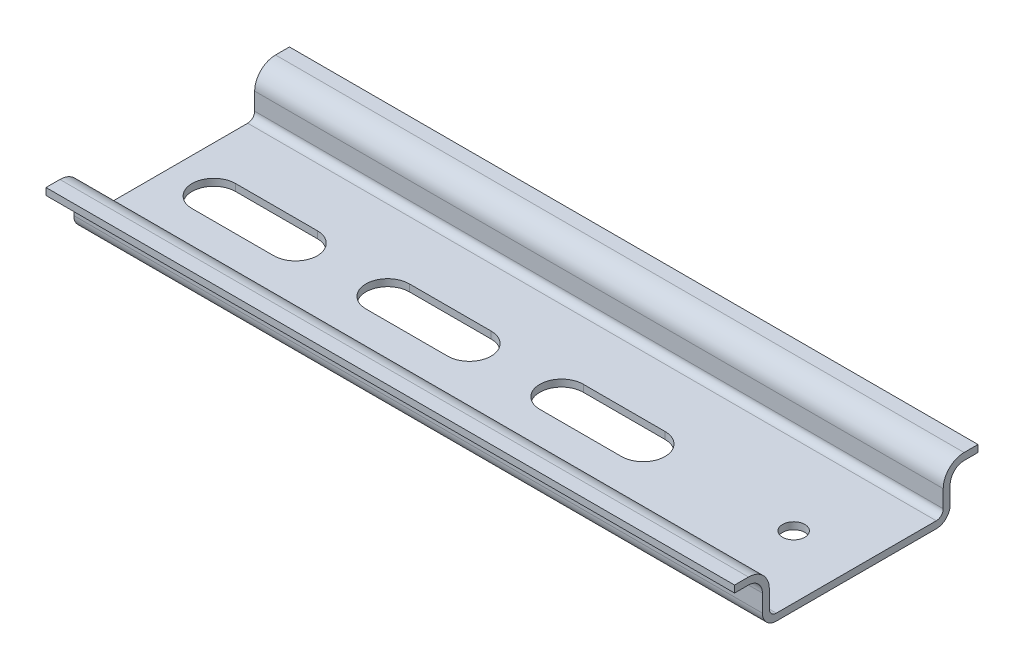
SolidWorks part; units mm, degrees
ref_plane "Front Plane" through (0, 0, 0) normal (0, 0, 1) x (1, 0, 0)
ref_plane "Top Plane" through (0, 0, 0) normal (0, 1, 0) x (1, 0, 0)
ref_plane "Right Plane" through (0, 0, 0) normal (1, 0, 0) x (0, 0, -1)
sketch "Sketch1" plane through (0, 0, 0) normal (1, 0, 0) x (0, 0, -1)
  line L0 (0, 0) -> (0, 18.2344) construction
  line L1 (0, 0) -> (26.621, 0) construction
  line L2 (-11.5, 0) -> (11.5, 0)
  line L3 (13.5, 2) -> (13.5, 4.5)
  line L4 (15.5, 6.5) -> (17.5, 6.5)
  line L5 (-13.5, 2) -> (-13.5, 4.5)
  line L6 (-15.5, 6.5) -> (-17.5, 6.5)
  arc A0 (13.5, 2) -> (11.5, 0) centre (11.5, 2) cw
  arc A1 (15.5, 6.5) -> (13.5, 4.5) centre (15.5, 4.5) ccw
  arc A2 (-13.5, 2) -> (-11.5, 0) centre (-11.5, 2) ccw
  arc A3 (-15.5, 6.5) -> (-13.5, 4.5) centre (-15.5, 4.5) cw
  point P9 (13.5, 0)
  dimension "D1" = 2
  dimension "D3" = 2
  dimension "D2" = 6.5
  dimension "D4" = 35
  dimension "D5" = 27
extrude "Extrude-Thin1" add sketch "Sketch1" along normal blind 61.5 and the other way blind 37.5 thin thin type one direction wall 1
sketch "Sketch2" plane through (0, 0, 0) normal (0, -1, 0) x (1, 0, 0)
  line L0 (0, 6.6969) -> (0, 0) construction
  line L1 (0, 0) -> (9.9599, 0) construction
  line L2 (-5.875, 3.125) -> (5.875, 3.125)
  line L3 (-5.875, -3.125) -> (5.875, -3.125)
  arc A0 (5.875, 3.125) -> (5.875, -3.125) centre (5.875, 0) cw
  arc A1 (-5.875, 3.125) -> (-5.875, -3.125) centre (-5.875, 0) ccw
  point P6 (0, 3.125)
  point P12 (0, -3.125)
  dimension "D2" = 11.75
  dimension "D1" = 6.25
extrude "Cut-Extrude1" cut sketch "Sketch2" against normal up to next
pattern_linear "LPattern1" count 2 spacing 25 along (1, 0, 0) count 2 spacing 25 along (-1, 0, 0) of "Cut-Extrude1"
sketch "Szkic1" plane through (0, 0, 0) normal (0, -1, 0) x (1, 0, 0)
  circle A0 centre (52.5, 0) radius 1.6
extrude "Wytnij-wyciągnięcie1" cut sketch "Szkic1" against normal through all
